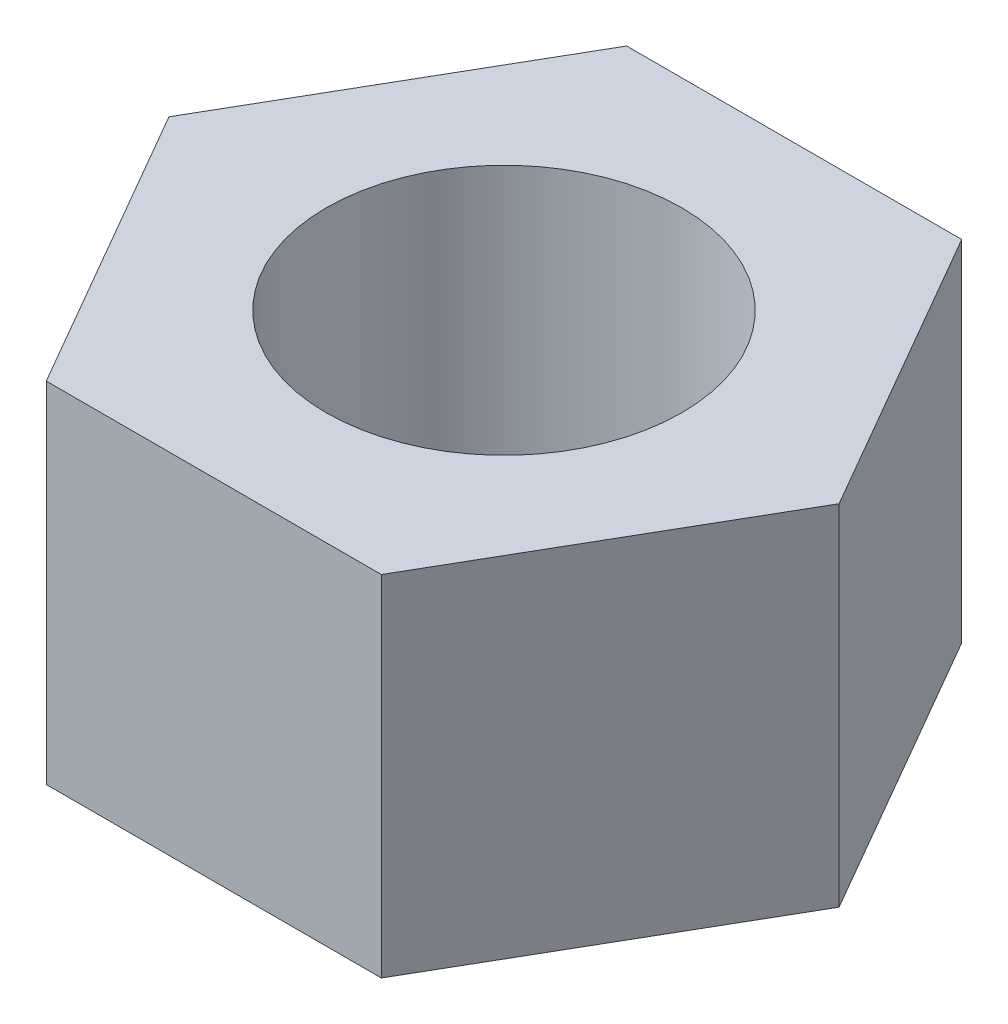
SolidWorks part; units mm, degrees
material "不锈钢 (铁素体)"
ref_plane "前视基准面" through (0, 0, 0) normal (0, 0, 1) x (1, 0, 0)
ref_plane "上视基准面" through (0, 0, 0) normal (0, 1, 0) x (1, 0, 0)
ref_plane "右视基准面" through (0, 0, 0) normal (1, 0, 0) x (0, 0, -1)
sketch "草图1" plane through (0, 0, 0) normal (0, 1, 0) x (1, 0, 0)
  line L1 (5.658, 0) -> (2.829, 4.9)
  line L2 (2.829, 4.9) -> (-2.829, 4.9)
  line L3 (-2.829, 4.9) -> (-5.658, 0)
  line L4 (-5.658, 0) -> (-2.829, -4.9)
  line L5 (-2.829, -4.9) -> (2.829, -4.9)
  line L6 (2.829, -4.9) -> (5.658, 0)
  circle A1 centre (0, 0) radius 4.9 construction
  circle A2 centre (0, 0) radius 3
  dimension "D2" = 6
  dimension "D1" = 9.8
extrude "凸台-拉伸1" add sketch "草图1" along normal blind 5.9
